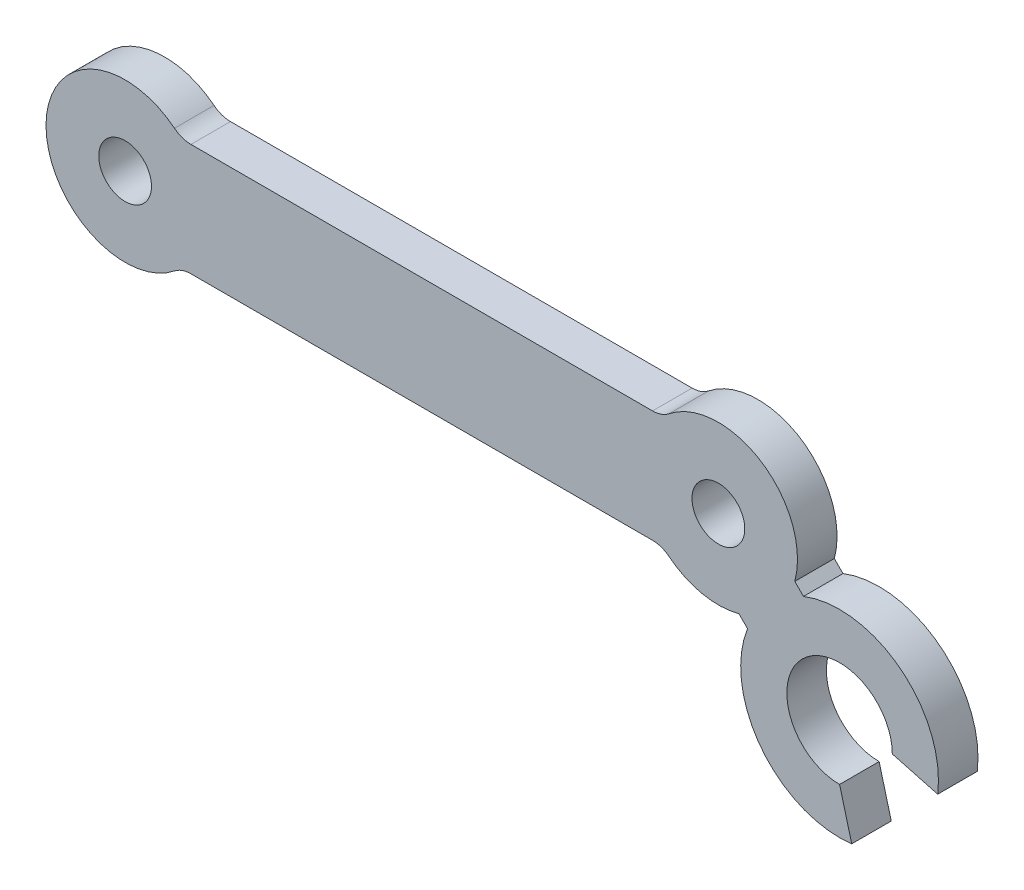
SolidWorks part; units mm, degrees
ref_plane "前视基准面" through (0, 0, 0) normal (0, 0, 1) x (1, 0, 0)
ref_plane "上视基准面" through (0, 0, 0) normal (0, 1, 0) x (1, 0, 0)
ref_plane "右视基准面" through (0, 0, 0) normal (1, 0, 0) x (0, 0, -1)
other "Configuration Table"
sketch "草图1" plane through (0, 0, 0) normal (0, 0, 1) x (1, 0, 0)
  line L0 (0, 0) -> (45, 0) construction
  line L1 (22.5, 0) -> (22.5, 4.25) construction
  line L2 (22.5, 0) -> (22.5, -4.25) construction
  line L3 (4.2353, 4.25) -> (4.2353, -4.25) construction
  line L4 (4.9937, 4.25) -> (40.0063, 4.25)
  line L5 (4.9937, -4.25) -> (40.0063, -4.25)
  line L6 (45, 0) -> (54.1924, -9.1924) construction
  line L7 (50.5847, -2.1935) -> (51.0104, -1.7678) construction
  line L8 (48.8891, -3.8891) -> (46.7678, -6.0104) construction
  line L9 (55.7321, 1.6294) -> (55.7629, 1.6448) construction
  line L10 (58.1924, -9.1924) -> (61.6354, -10.1149)
  line L11 (60.9288, 2.57) -> (60.9597, 2.6009) construction
  line L12 (54.1924, -13.1924) -> (55.1149, -16.6354)
  line L13 (51.0104, -1.7678) -> (51.4532, -2.2105)
  line L14 (51.0104, -1.7678) -> (50.7956, -1.5529)
  line L15 (46.7678, -6.0104) -> (47.2105, -6.4532)
  line L16 (46.7678, -6.0104) -> (46.5529, -5.7956)
  line L17 (50.5847, -2.1935) -> (48.8891, -3.8891) construction
  circle A0 centre (0, 0) radius 2
  arc A1 (3.7453, 4.6875) -> (3.7453, -4.6875) centre (0, 0) ccw
  arc A2 (4.9937, 4.25) -> (3.7453, 4.6875) centre (4.9937, 6.25) cw
  arc A3 (4.9937, -4.25) -> (3.7453, -4.6875) centre (4.9937, -6.25) ccw
  circle A4 centre (45, 0) radius 2
  arc A5 (40.0063, -4.25) -> (41.2547, -4.6875) centre (40.0063, -6.25) cw
  arc A6 (40.0063, 4.25) -> (41.2547, 4.6875) centre (40.0063, 6.25) ccw
  arc A7 (41.2547, 4.6875) -> (50.7956, -1.5529) centre (45, 0) cw
  arc A8 (47.2105, -6.4532) -> (55.1149, -16.6354) centre (54.1924, -9.1924) ccw
  arc A9 (46.5529, -5.7956) -> (41.2547, -4.6875) centre (45, 0) cw
  arc A10 (58.1924, -9.1924) -> (54.1924, -13.1924) centre (54.1924, -9.1924) ccw
  arc A11 (61.6354, -10.1149) -> (51.4532, -2.2105) centre (54.1924, -9.1924) ccw
  dimension "D1" = 2
  dimension "D2" = 2
  dimension "D4" = 60
  dimension "D6" = 4
  dimension "D7" = 6
  dimension "D10" = 4
  dimension "D12" = 7.5
  dimension "D3" = 135
  dimension "D5" = 45
  dimension "D8" = 8.5
  dimension "D9" = 6
  dimension "D11" = 13
extrude "凸台-拉伸1" add sketch "草图1" along normal blind 3
